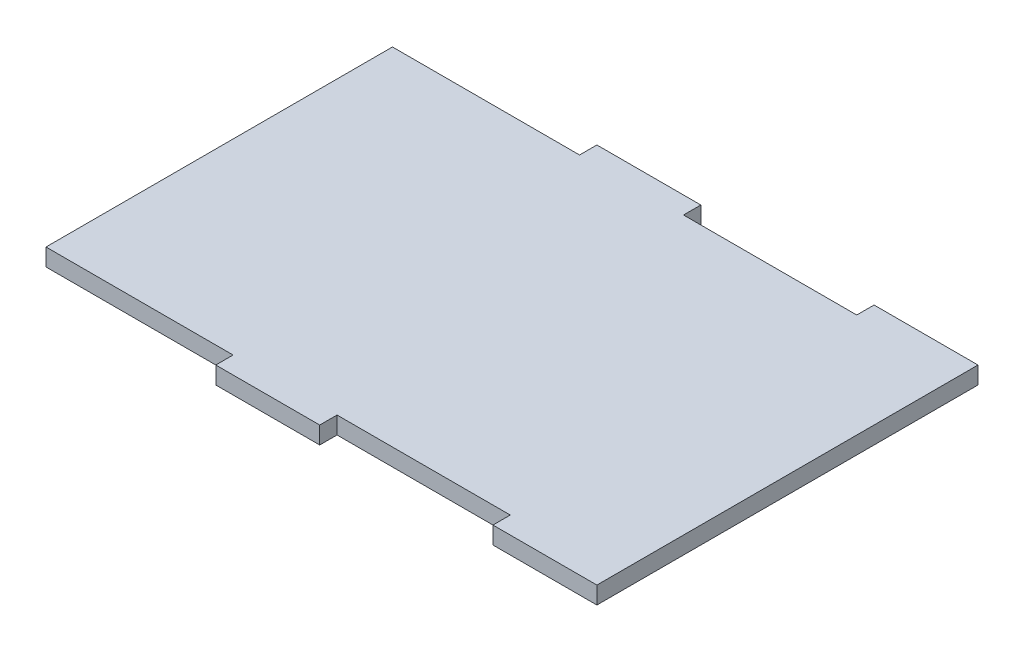
SolidWorks part; units mm, degrees
ref_plane "Front Plane" through (0, 0, 0) normal (0, 0, 1) x (1, 0, 0)
ref_plane "Top Plane" through (0, 0, 0) normal (0, 1, 0) x (1, 0, 0)
ref_plane "Right Plane" through (0, 0, 0) normal (1, 0, 0) x (0, 0, -1)
sketch "Sketch1" plane through (0, 0, 0) normal (0, 1, 0) x (1, 0, 0)
  line L0 (104.14, 63.5) -> (104.14, 66.675)
  line L1 (0, 0) -> (34.29, 0)
  line L2 (0, 0) -> (0, 63.5)
  line L3 (0, 63.5) -> (34.29, 63.5)
  line L4 (104.14, 0) -> (104.14, 63.5)
  line L5 (104.14, 66.675) -> (85.09, 66.675)
  line L6 (85.09, 66.675) -> (85.09, 63.5)
  line L7 (53.34, 63.5) -> (53.34, 66.675)
  line L8 (53.34, 66.675) -> (34.29, 66.675)
  line L9 (34.29, 66.675) -> (34.29, 63.5)
  line L10 (53.34, 63.5) -> (85.09, 63.5)
  line L11 (0, 31.75) -> (104.14, 31.75) construction
  line L12 (34.29, -3.175) -> (34.29, 0)
  line L13 (53.34, -3.175) -> (34.29, -3.175)
  line L14 (53.34, 0) -> (53.34, -3.175)
  line L15 (85.09, -3.175) -> (85.09, 0)
  line L16 (104.14, -3.175) -> (85.09, -3.175)
  line L17 (104.14, 0) -> (104.14, -3.175)
  line L18 (53.34, 0) -> (85.09, 0)
  dimension "D1" = 104.14
  dimension "D2" = 63.5
  dimension "D3" = 19.05
  dimension "D5" = 3.175
  dimension "D4" = 2
extrude "Boss-Extrude1" add sketch "Sketch1" along normal blind 3.175
